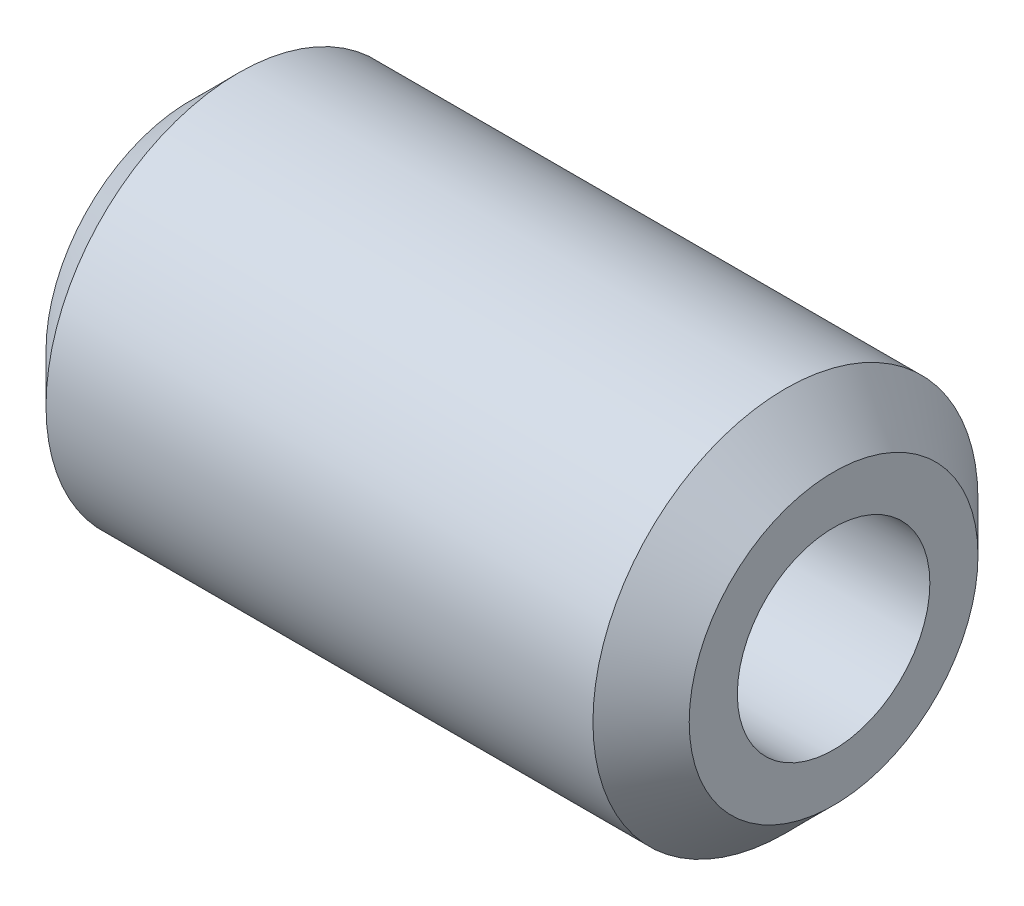
SolidWorks part; units mm, degrees
ref_plane "Front Plane" through (0, 0, 0) normal (0, 0, 1) x (1, 0, 0)
ref_plane "Top Plane" through (0, 0, 0) normal (0, 1, 0) x (1, 0, 0)
ref_plane "Right Plane" through (0, 0, 0) normal (1, 0, 0) x (0, 0, -1)
sketch "Sketch1" plane through (0, 0, 0) normal (0, 0, 1) x (1, 0, 0)
  line L0 (-73.004, 0) -> (55.1955, 0) construction
  line L1 (-18.375, 5.5) -> (-18.375, 8.25)
  line L2 (-18.375, 8.25) -> (-15.625, 11)
  line L3 (-15.625, 11) -> (15.625, 11)
  line L4 (15.625, 11) -> (18.375, 8.25)
  line L5 (18.375, 8.25) -> (18.375, 5.5)
  line L6 (18.375, 5.5) -> (-18.375, 5.5)
  line L7 (0, 5.5) -> (0, 0) construction
  line L8 (0, 5.5) -> (0, 11) construction
  line L9 (-18.375, 8.25) -> (18.375, 8.25) construction
  point P4 (-8.7878, 13.6181)
  point P13 (-13.8593, 10.1423)
  dimension "D1" = 5.5
  dimension "D2" = 36.75
  dimension "D3" = 8.25
  dimension "D4" = 2.75
  dimension "D5" = 45
revolve "Revolve1" add sketch "Sketch1" angle 360 about L0
